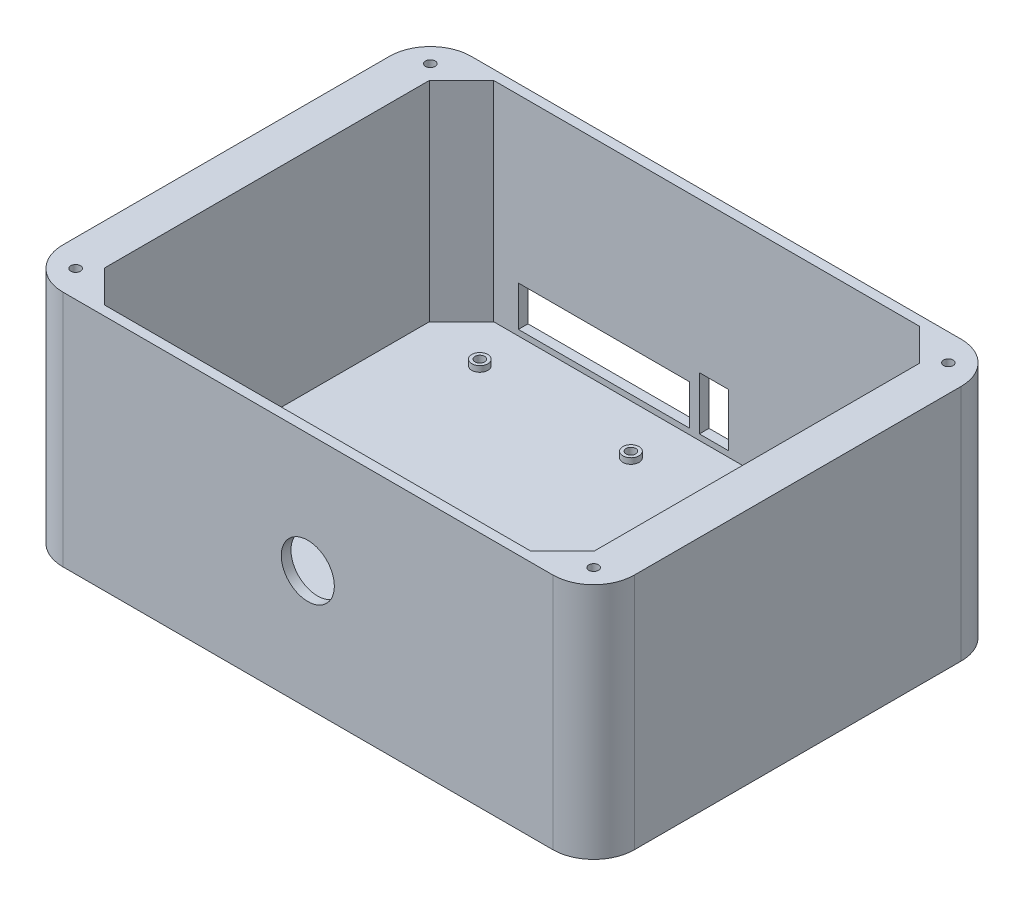
SolidWorks part; units mm, degrees
ref_plane "Front Plane" through (0, 0, 0) normal (0, 0, 1) x (1, 0, 0)
ref_plane "Top Plane" through (0, 0, 0) normal (0, 1, 0) x (1, 0, 0)
ref_plane "Right Plane" through (0, 0, 0) normal (1, 0, 0) x (0, 0, -1)
sketch "Sketch1" plane through (0, 0, 0) normal (0, 1, 0) x (1, 0, 0)
  line L1 (-76.2, 63.5) -> (76.2, 63.5)
  line L2 (-88.9, 50.8) -> (-88.9, -50.8)
  line L3 (-76.2, -63.5) -> (76.2, -63.5)
  line L4 (88.9, 50.8) -> (88.9, -50.8)
  line L5 (-88.9, 63.5) -> (88.9, -63.5) construction
  line L6 (-88.9, -63.5) -> (88.9, 63.5) construction
  arc A0 (-76.2, 63.5) -> (-88.9, 50.8) centre (-76.2, 50.8) ccw
  arc A1 (-88.9, -50.8) -> (-76.2, -63.5) centre (-76.2, -50.8) ccw
  arc A2 (76.2, -63.5) -> (88.9, -50.8) centre (76.2, -50.8) ccw
  arc A3 (76.2, 63.5) -> (88.9, 50.8) centre (76.2, 50.8) cw
  point P0 (0, 0)
  dimension "D3" = 12.7
  dimension "D1" = 177.8
  dimension "D2" = 127
extrude "Boss-Extrude1" add sketch "Sketch1" along normal blind 9
sketch "Sketch2" plane through (0, 9, 0) normal (0, 1, 0) x (1, 0, 0)
  line L0 (76.2, 63.5) -> (-76.2, 63.5) construction
  line L1 (88.9, -50.8) -> (88.9, 50.8) construction
  line L2 (-76.2, -63.5) -> (76.2, -63.5) construction
  line L3 (-88.9, 50.8) -> (-88.9, -50.8) construction
  line L4 (76.2, 63.5) -> (-76.2, 63.5)
  line L5 (88.9, -50.8) -> (88.9, 50.8)
  line L6 (-76.2, -63.5) -> (76.2, -63.5)
  line L7 (-88.9, 50.8) -> (-88.9, -50.8)
  line L8 (76.2, 60.5) -> (-76.2, 60.5)
  line L10 (-76.2, -60.5) -> (76.2, -60.5)
  line L16 (-76.2, 60.5) -> (-76.2, -60.5)
  line L17 (76.2, 60.5) -> (76.2, -60.5)
  line L19 (-85.9, 50.8) -> (-85.9, -50.8) construction
  line L20 (85.9, -50.8) -> (85.9, 50.8) construction
  arc A0 (88.9, 50.8) -> (76.2, 63.5) centre (76.2, 50.8) ccw construction
  arc A1 (76.2, -63.5) -> (88.9, -50.8) centre (76.2, -50.8) ccw construction
  arc A2 (-88.9, -50.8) -> (-76.2, -63.5) centre (-76.2, -50.8) ccw construction
  arc A3 (-76.2, 63.5) -> (-88.9, 50.8) centre (-76.2, 50.8) ccw construction
  arc A4 (88.9, 50.8) -> (76.2, 63.5) centre (76.2, 50.8) ccw
  arc A5 (76.2, -63.5) -> (88.9, -50.8) centre (76.2, -50.8) ccw
  arc A6 (-88.9, -50.8) -> (-76.2, -63.5) centre (-76.2, -50.8) ccw
  arc A7 (-76.2, 63.5) -> (-88.9, 50.8) centre (-76.2, 50.8) ccw
  arc A12 (-76.2, 60.5) -> (-85.9, 50.8) centre (-76.2, 50.8) ccw construction
  arc A13 (85.9, 50.8) -> (76.2, 60.5) centre (76.2, 50.8) ccw construction
  arc A14 (76.2, -60.5) -> (85.9, -50.8) centre (76.2, -50.8) ccw construction
  arc A15 (-85.9, -50.8) -> (-76.2, -60.5) centre (-76.2, -50.8) ccw construction
  dimension "D1" = 3
extrude "Boss-Extrude2" add sketch "Sketch2" along normal blind 65
chamfer "Chamfer1" distance 10 angle 45 4 edges at (76.2, 41.5, 60.5) (-76.2, 41.5, 60.5) (76.2, 41.5, -60.5) (-76.2, 41.5, -60.5)
sketch "Sketch3" plane through (0, 0, -60.5) normal (0, 0, 1) x (1, 0, 0)
  line L1 (-58.5224, 10.7807) -> (-5.2224, 10.7807)
  line L2 (-58.5224, 10.7807) -> (-58.5224, 23.2807)
  line L3 (-58.5224, 23.2807) -> (-5.2224, 23.2807)
  line L4 (-5.2224, 10.7807) -> (-5.2224, 23.2807)
  dimension "D1" = 12.5
  dimension "D2" = 53.3
extrude "Cut-Extrude1" cut sketch "Sketch3" against normal through all contours L2 L1 L4 L3
sketch "Sketch4" plane through (0, 9, 0) normal (0, 1, 0) x (1, 0, 0)
  circle A0 centre (-56.5115, 46.5) radius 2.5
  circle A1 centre (-8.2115, 45.2) radius 2.5
  circle A2 centre (-23.4115, -5.6) radius 2.5
  circle A3 centre (-51.3115, -5.6) radius 2.5
  point P4 (0, 0)
  dimension "D3" = 5
  dimension "D6" = 5
  dimension "D11" = 5
  dimension "D12" = 5
  dimension "D7" = 1.3
  dimension "D9" = 50.8
  dimension "D10" = 15.2
  dimension "D13" = 27.9
extrude "Boss-Extrude3" add sketch "Sketch4" along normal up to surface (1.7807 mm away) up to face at (-31.8724, 10.7807, -62)
sketch "Sketch5" plane through (0, 10.7807, 0) normal (0, 1, 0) x (1, 0, 0)
  circle A3 centre (-23.4115, -5.6) radius 1.5
  circle A4 centre (-23.4115, -5.6) radius 1.5
  circle A6 centre (-51.3115, -5.6) radius 1.5
  circle A7 centre (-51.3115, -5.6) radius 1.5
  circle A9 centre (-56.5115, 46.5) radius 1.5
  circle A10 centre (-56.5115, 46.5) radius 1.5
  circle A12 centre (-8.2115, 45.2) radius 1.5
  circle A13 centre (-8.2115, 45.2) radius 1.5
  dimension "D1" = 1
  dimension "D2" = 1
  dimension "D3" = 1
  dimension "D4" = 1
extrude "Cut-Extrude4" cut sketch "Sketch5" along normal blind 3 and the other way blind 3
sketch "Sketch7" plane through (0, 0, -60.5) normal (0, 0, 1) x (1, 0, 0)
  line L0 (-58.5224, 10.7807) -> (-5.2224, 10.7807) construction
  line L1 (6.7776, 27.2807) -> (-2.2224, 27.2807)
  line L2 (6.7776, 27.2807) -> (6.7776, 10.7807)
  line L3 (6.7776, 10.7807) -> (-2.2224, 10.7807)
  line L4 (-2.2224, 27.2807) -> (-2.2224, 10.7807)
  line L5 (-5.2224, 10.7807) -> (-5.2224, 23.2807) construction
  dimension "D1" = 16.5
  dimension "D2" = 0
  dimension "16" = 9
  dimension "D3" = 3
extrude "Cut-Extrude6" cut sketch "Sketch7" against normal blind 3 and the other way blind 3
sketch "Sketch8" plane through (0, 0, 63.5) normal (0, 0, 1) x (1, 0, 0)
  line L0 (0, 0) -> (0, 74) construction
  line L1 (-76.2, 74) -> (76.2, 74) construction
  circle A0 centre (0, 37) radius 8.25
  dimension "D1" = 16.5
extrude "Cut-Extrude7" cut sketch "Sketch8" against normal blind 3
sketch "Sketch9" plane through (0, 74, 0) normal (0, 1, 0) x (1, 0, 0)
  line L0 (-85.1803, -59.7803) -> (-61.0288, -35.6288) construction
  line L1 (-40.7, 0) -> (40.7, 0) construction
  line L2 (0, -40.7) -> (0, 40.7) construction
  line L3 (85.1803, -59.7803) -> (61.0288, -35.6288) construction
  arc A0 (-88.9, -50.8) -> (-76.2, -63.5) centre (-76.2, -50.8) ccw construction
  circle A1 centre (-80.5558, -55.1558) radius 1.5
  circle A2 centre (-80.5558, 55.1558) radius 1.5
  circle A3 centre (29.7558, -55.1558) radius 1.5
  circle A4 centre (80.5558, 55.1558) radius 1.5
  circle A5 centre (80.5558, -55.1558) radius 1.5
  dimension "D2" = 3
  dimension "D1" = 6.54
extrude "Cut-Extrude8" cut sketch "Sketch9" against normal blind 20
